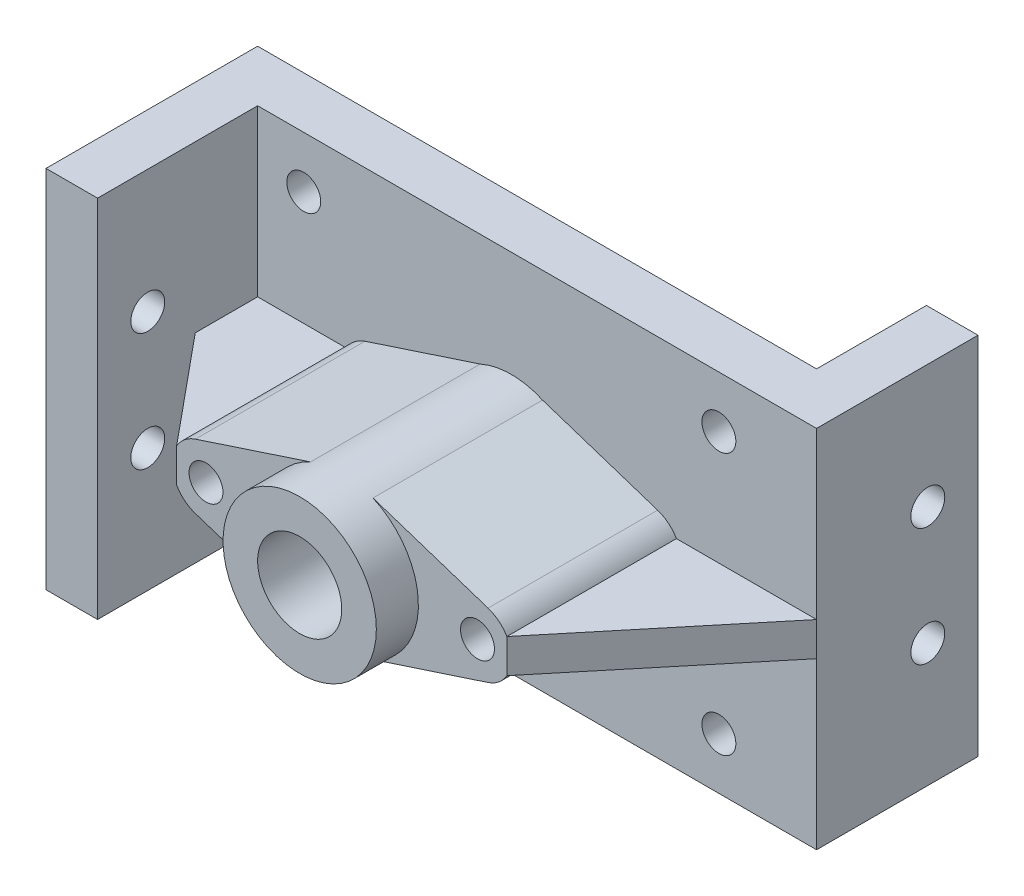
SolidWorks part; units mm, degrees
ref_plane "Front Plane" through (0, 0, 0) normal (0, 0, 1) x (1, 0, 0)
ref_plane "Top Plane" through (0, 0, 0) normal (0, 1, 0) x (1, 0, 0)
ref_plane "Right Plane" through (0, 0, 0) normal (1, 0, 0) x (0, 0, -1)
sketch "Sketch1" plane through (0, 0, 0) normal (0, 1, 0) x (1, 0, 0)
  line L0 (0, 0) -> (0, 1.56)
  line L1 (0, 1.56) -> (4.12, 1.56)
  line L2 (4.12, 1.56) -> (4.12, 2.37)
  line L3 (4.12, 2.37) -> (4.5, 2.37)
  line L4 (4.5, 2.37) -> (4.5, 1.18)
  line L5 (0, 0) -> (0.38, 0)
  line L6 (0.38, 0) -> (0.38, 1.18)
  line L7 (0.38, 1.18) -> (4.5, 1.18)
  dimension "D1" = 1.56
  dimension "D2" = 4.12
  dimension "D3" = 0.81
  dimension "D4" = 0.38
  dimension "D5" = 1.19
  dimension "D6" = 0.38
extrude "Boss-Extrude1" add sketch "Sketch1" along normal blind 2.69 contours L7 L4 L3 L2 L1 L0 L5 L6
sketch "Sketch2" plane through (0, 0, -1.18) normal (0, 0, 1) x (1, 0, 0)
  line L0 (4.5, 2.69) -> (4.5, 2.31)
  line L1 (4.5, 2.69) -> (4.5, 0) construction
  line L2 (4.5, 2.31) -> (3.78, 2.31)
  line L3 (4.5, 1.345) -> (0.38, 1.345)
  line L4 (0.38, 2.69) -> (0.38, 0) construction
  line L5 (2.44, 2.69) -> (2.44, 0)
  line L6 (0.38, 2.69) -> (4.5, 2.69) construction
  line L7 (0.38, 0) -> (4.5, 0) construction
  line L8 (3.78, 2.31) -> (0.72, 2.31)
  circle A0 centre (3.78, 2.31) radius 0.125
  circle A1 centre (3.78, 0.38) radius 0.125
  circle A2 centre (0.72, 2.31) radius 0.125
  circle A3 centre (0.72, 0.38) radius 0.125
  dimension "D3" = 0.25
  dimension "D4" = 3.06
  dimension "D5" = 0.25
  dimension "D1" = 0.38
  dimension "D2" = 0.72
sketch "Sketch3" plane through (4.5, 0, 0) normal (1, 0, 0) x (0, 0, -1)
  line L0 (2.37, 2.69) -> (2.37, 1.78)
  line L1 (2.37, 2.69) -> (2.37, 0) construction
  line L2 (2.37, 1.78) -> (2, 1.78)
  line L3 (2.37, 1.345) -> (1.18, 1.345)
  line L4 (2, 1.78) -> (2, 0.91)
  circle A0 centre (2, 1.78) radius 0.125
  circle A1 centre (2, 0.91) radius 0.125
  dimension "D3" = 0.25
  dimension "D1" = 0.91
  dimension "D2" = 0.37
  dimension "D4" = 0.87
extrude "Cut-Extrude2" cut sketch "Sketch3" against normal blind 10 contours A0 | A1
sketch "Sketch5" plane through (0.38, 0, 0) normal (1, 0, 0) x (0, 0, -1)
  line L0 (0, 2.69) -> (0, 1.78)
  line L1 (0, 2.69) -> (0, 0) construction
  line L2 (0, 1.78) -> (0.37, 1.78)
  line L3 (0, 1.345) -> (1.18, 1.345)
  line L4 (1.18, 2.69) -> (1.18, 0) construction
  circle A0 centre (0.37, 1.78) radius 0.125
  circle A1 centre (0.37, 0.91) radius 0.125
  dimension "D3" = 0.25
  dimension "D1" = 0.37
  dimension "D2" = 0.91
extrude "Cut-Extrude4" cut sketch "Sketch5" against normal blind 10 contours A0 | A1
extrude "Cut-Extrude5" cut sketch "Sketch2" against normal blind 10 contours A1 | A0 | A3 | A2
sketch "Sketch6" plane through (0, 0, -1.18) normal (0, 0, 1) x (1, 0, 0)
  line L0 (0.72, 2.31) -> (3.78, 2.31)
  line L1 (3.78, 2.31) -> (3.78, 0.38)
  line L2 (3.78, 0.38) -> (0.72, 0.38)
  line L3 (2.25, 2.31) -> (2.25, 0.38)
  line L4 (3.78, 1.345) -> (3.78, 1.47)
  line L5 (3.78, 1.345) -> (3.78, 1.22)
  line L6 (0.72, 2.31) -> (0.72, 0.38)
  line L7 (3.78, 1.47) -> (0.72, 1.47)
  line L8 (3.78, 1.345) -> (0.72, 1.345)
  line L9 (3.78, 1.22) -> (0.72, 1.22)
  line L10 (3.78, 1.47) -> (4.5, 1.47)
  line L11 (4.5, 2.69) -> (4.5, 0) construction
  line L12 (4.5, 1.47) -> (4.5, 1.22)
  line L13 (4.5, 1.22) -> (0.38, 1.22)
  line L14 (0.38, 2.69) -> (0.38, 0) construction
  line L15 (0.38, 1.22) -> (0.38, 1.47)
  line L16 (0.38, 1.47) -> (4.5, 1.47)
  circle A0 centre (2.25, 1.345) radius 0.565
  dimension "D4" = 1.13
  dimension "D1" = 0.125
  dimension "D2" = 0.125
  dimension "D3" = 0.25
extrude "Boss-Extrude2" add sketch "Sketch6" along normal blind 1.56 contours A0
sketch "Sketch8" plane through (0, 0, 0.38) normal (0, 0, 1) x (1, 0, 0)
  circle A0 centre (2.25, 1.345) radius 0.31
  dimension "D1" = 0.62
extrude "Cut-Extrude6" cut sketch "Sketch8" against normal blind 10
sketch "Sketch9" plane through (0, 0, -1.18) normal (0, 0, 1) x (1, 0, 0)
  line L0 (2.25, 1.345) -> (3.5, 1.345)
  line L1 (3.5, 1.345) -> (3.5, 1.22)
  line L2 (3.5, 1.22) -> (4.5, 1.22)
  line L3 (4.5, 2.69) -> (4.5, 0) construction
  line L4 (4.5, 1.22) -> (4.5, 1.47)
  line L5 (4.5, 1.47) -> (3.5, 1.47)
  line L6 (3.5, 1.47) -> (3.5, 1.345)
  dimension "D1" = 1.25
  dimension "D2" = 0.125
  dimension "D3" = 0.25
  dimension "D4" = 0.125
sketch "Sketch14" plane through (0, 0, -1.18) normal (0, 0, 1) x (1, 0, 0)
  line L0 (2.25, 1.345) -> (2.25, 2.69)
  line L2 (3.3284, 1.1072) -> (2.3647, 0.7918)
  line L3 (3.3286, 1.5823) -> (2.3704, 1.897)
  line L4 (0.38, 2.69) -> (4.5, 2.69) construction
  line L5 (2.25, 2.69) -> (2.25, 0)
  line L6 (0.38, 0) -> (4.5, 0) construction
  line L7 (1.1716, 1.1072) -> (2.1353, 0.7918)
  line L8 (1.1714, 1.5823) -> (2.1296, 1.897)
  arc A0 (3.3286, 1.5823) -> (3.3284, 1.1072) centre (3.2506, 1.3448) cw
  circle A1 centre (2.25, 1.345) radius 0.565 construction
  arc A2 (2.3704, 1.897) -> (2.3647, 0.7918) centre (2.25, 1.345) cw
  circle A3 centre (2.25, 1.345) radius 0.565
  arc A4 (2.3704, 1.897) -> (2.3647, 0.7918) centre (2.25, 1.345) ccw
  arc A5 (2.1296, 1.897) -> (2.1353, 0.7918) centre (2.25, 1.345) ccw
  arc A6 (1.1714, 1.5823) -> (1.1716, 1.1072) centre (1.2494, 1.3448) ccw
  dimension "D2" = 0.25
  dimension "D3" = 0.9582
  dimension "D1" = 0
extrude "Boss-Extrude7" add sketch "Sketch14" along normal blind 1.25
sketch "Sketch16" plane through (0, 0, -1.18) normal (0, 0, 1) x (1, 0, 0)
  line L1 (0.38, 2.69) -> (4.5, 2.69) construction
  line L2 (2.25, 2.69) -> (2.25, 0)
  line L3 (0.38, 0) -> (4.5, 0) construction
ref_plane "Plane1" through (2.25, 0, 0) normal (-1, 0, 0) x (0, 0, 1)
mirror "Mirror2" about plane through (2.25, 0, 0) normal (-1, 0, 0) of "Boss-Extrude7"
sketch "Sketch22" plane through (0, 0, 0.07) normal (0, 0, 1) x (1, 0, 0)
  circle A0 centre (3.2506, 1.3448) radius 0.125
  dimension "D1" = 0.25
extrude "Cut-Extrude8" cut sketch "Sketch22" against normal blind 10
sketch "Sketch23" plane through (0, 0, 0.07) normal (0, 0, 1) x (1, 0, 0)
  circle A0 centre (1.2494, 1.3448) radius 0.125
  dimension "D1" = 0.25
extrude "Cut-Extrude9" cut sketch "Sketch23" against normal blind 10
sketch "Sketch25" plane through (0, 0, -1.18) normal (0, 0, 1) x (1, 0, 0)
  line L0 (4.5, 1.47) -> (3.4002, 1.47)
  line L1 (4.5, 1.47) -> (4.5, 1.22)
  line L2 (4.5, 1.22) -> (3.4002, 1.22)
  line L3 (3.4002, 1.22) -> (3.4002, 1.47)
extrude "Boss-Extrude8" add sketch "Sketch25" along normal blind 1.25
mirror "Mirror3" about plane through (2.25, 0, 0) normal (-1, 0, 0) of "Boss-Extrude8"
sketch "Sketch27" plane through (0, 1.47, 0) normal (0, 1, 0) x (1, 0, 0)
  line L0 (3.467, -0.07) -> (4.5, 1.18)
  line L1 (3.467, -0.07) -> (4.5, -0.07)
  line L2 (4.5, -0.07) -> (4.5, 1.18)
extrude "Cut-Extrude13" cut sketch "Sketch27" against normal blind 0.25
mirror "Mirror4" about plane through (2.25, 0, 0) normal (-1, 0, 0) of "Cut-Extrude13"
sketch "Sketch30" plane through (0, 0, 0) normal (-1, 0, 0) x (0, 0, 1)
  line L0 (0, 1.22) -> (0, 1.47)
  line L9 (0, 0) -> (0, 1.22)
  line L10 (0, 1.22) -> (-1.18, 1.22)
  line L11 (-1.18, 1.22) -> (-1.18, 1.47)
  line L12 (-1.18, 1.47) -> (0, 1.47)
  line L13 (0, 1.47) -> (0, 2.69)
  line L14 (0, 2.69) -> (-1.56, 2.69)
  line L15 (-1.56, 2.69) -> (-1.56, 0)
  line L16 (-1.56, 0) -> (0, 0)
  line L18 (0, 1.22) -> (-1.18, 1.22)
  line L19 (-1.18, 1.22) -> (-1.18, 1.47)
  line L20 (-1.18, 1.47) -> (0, 1.47)
  dimension "D1" = 0
extrude "Boss-Extrude10" add sketch "Sketch30" against normal blind 0.38
